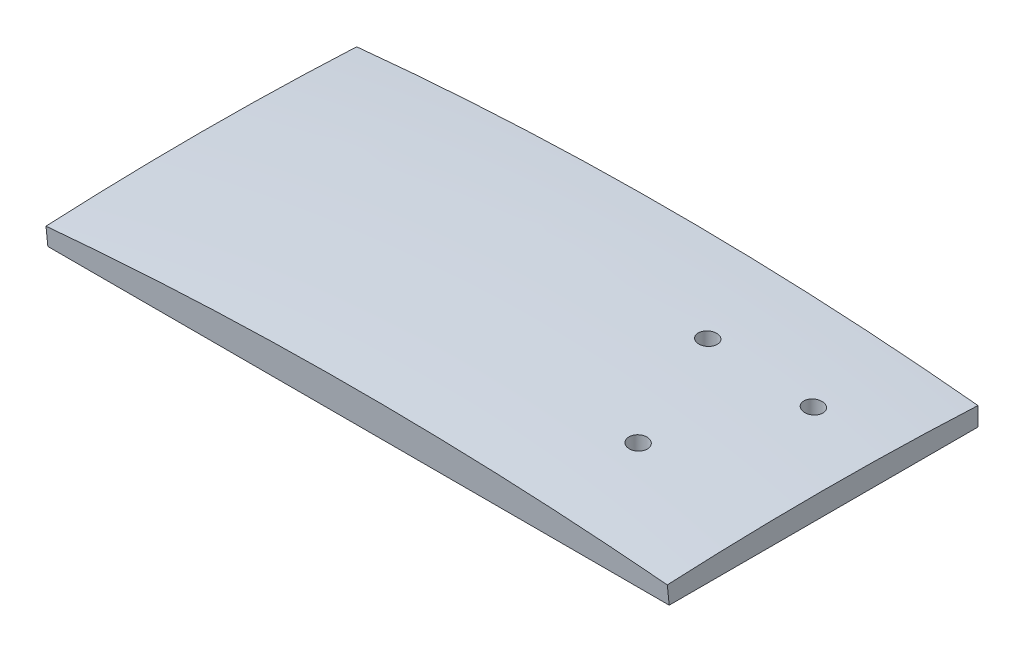
SolidWorks part; units mm, degrees
ref_plane "Спереди" through (0, 0, 0) normal (0, 0, 1) x (1, 0, 0)
ref_plane "Сверху" through (0, 0, 0) normal (0, 1, 0) x (1, 0, 0)
ref_plane "Справа" through (0, 0, 0) normal (1, 0, 0) x (0, 0, -1)
sketch "Эскиз1" plane through (0, 0, 0) normal (0, 0, 1) x (1, 0, 0)
  line L0 (0, 0) -> (100, 0)
  line L1 (100, 0) -> (100, 3)
  line L2 (0, 0) -> (0, 3)
  arc A0 (100, 3) -> (0, 3) centre (50, -494.4937) ccw
  point P6 (0, 0)
  point P7 (0, 0)
  point P8 (0, 0)
  point P9 (0, 0)
  dimension "D2" = 1000
  dimension "D1" = 100
  dimension "D3" = 3
sketch "Эскиз3" plane through (0, 0, 0) normal (1, 0, 0) x (0, 0, -1)
  line L0 (0, 3) -> (-50, 3) construction
  arc A0 (0, 3) -> (-50, 3) centre (-25, -496.3746) ccw
  point P2 (-50, 3)
  point P5 (0, 0)
  point P7 (0, 0)
  point P8 (0, 0)
  point P9 (0, 0)
  point P10 (0, 0)
  point P11 (0, 0)
  dimension "D1" = 1000
  dimension "D2" = 50
sweep "По траектории3" add profiles "Эскиз1" path "Эскиз3"
sketch "Эскиз6" plane through (0, 0, 0) normal (-1, 0, 0) x (0, 0, 1)
  line L0 (0, 0) -> (49.7004, 0.015)
  line L1 (49.7004, 0.015) -> (50, 3)
  line L2 (50, 3) -> (0, 3)
  line L3 (0, 3) -> (0, 0)
extrude "Бобышка-Вытянуть2" add sketch "Эскиз6" against normal blind 100
sketch "Эскиз7" plane through (0, 0, 0) normal (0, -1, 0.0003) x (1, 0, 0)
  line L0 (50, 49.7004) -> (50, 0) construction
  line L1 (0, 49.7004) -> (100, 49.7004) construction
  line L2 (0, 0) -> (100, 0) construction
  line L3 (80, 49.7004) -> (80, 34.7004) construction
  line L5 (100, 0) -> (100, 49.7004) construction
  line L7 (70, 15) -> (50, 15) construction
  line L8 (90, 15) -> (100, 15) construction
  line L9 (71.5, 15) -> (71.5, 0) construction
  line L10 (88.5, 15) -> (88.5, 0) construction
  line L11 (71.5, 15) -> (88.5, 15) construction
  line L12 (80, 15) -> (80, 44.9476) construction
  circle A0 centre (80, 34.7004) radius 1.5
  circle A1 centre (71.5, 15) radius 1.5
  circle A2 centre (88.5, 15) radius 1.5
  point P8 (0, 0)
  dimension "D1" = 3
  dimension "D2" = 15
  dimension "D4" = 10
  dimension "D5" = 20
extrude "Вырез-Вытянуть1" cut sketch "Эскиз7" against normal blind 100
